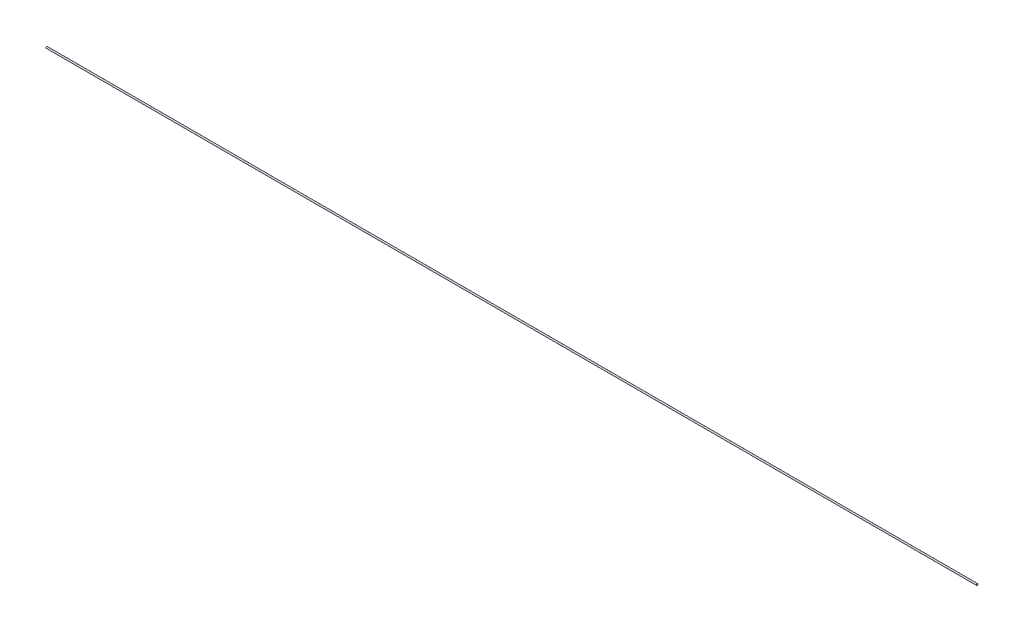
SolidWorks part; units mm, degrees
ref_plane "Front" through (0, 0, 0) normal (0, 0, 1) x (1, 0, 0)
ref_plane "Top" through (0, 0, 0) normal (0, 1, 0) x (1, 0, 0)
ref_plane "Right" through (0, 0, 0) normal (1, 0, 0) x (0, 0, -1)
sketch "Sketch1" plane through (0, 0, 0) normal (1, 0, 0) x (0, 0, -1)
  circle A0 centre (0, 0) radius 6.35
  circle A1 centre (0, 0) radius 5.842
  point P4 (6.35, 0)
  point P5 (5.842, 0)
  dimension "OD" = 12.7
  dimension "ID" = 11.684
  dimension "Wall" = 0.508
sketch "Sketch4" plane through (0, 0, 0) normal (1, 0, 0) x (0, 0, -1)
  circle A0 centre (0, 0) radius 6.35 construction
  circle A1 centre (0, 0) radius 6.35
  circle A2 centre (0, 0) radius 5.842 construction
  circle A3 centre (0, 0) radius 5.842
extrude "Boss-Extrude1" add sketch "Sketch4" along normal mid plane 7620
sketch "Sketch2" plane through (0, 0, 0) normal (0, 0, 1) x (1, 0, 0)
  line L0 (-3810, 0) -> (3810, 0) construction
  line L2 (-3810, 6.35) -> (-3810, -6.35) construction
  point P5 (-3575.4733, 0)
  point P6 (3575.4733, 0)
  dimension "D1" = 234.5267
  dimension "D2" = 234.5267
equation "\"D1@Sketch2\"=.9+(\"length@Boss-Extrude1\"/36)"
equation "\"D2@Sketch2\"=\"D1@Sketch2\""
